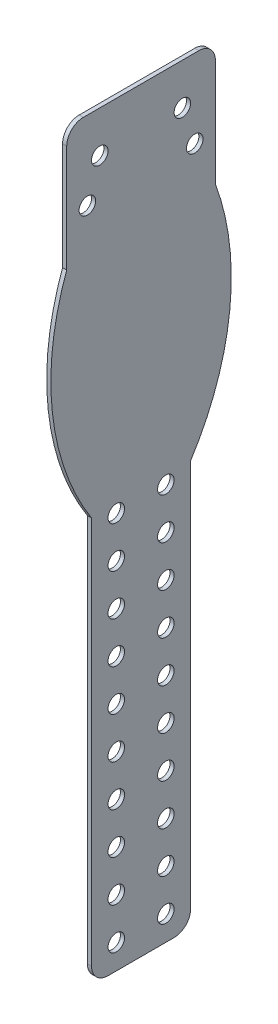
SolidWorks part; units mm, degrees
material "PVC 0.007 Plasticized"
ref_plane "Front Plane" through (0, 0, 0) normal (0, 0, 1) x (1, 0, 0)
ref_plane "Top Plane" through (0, 0, 0) normal (0, 1, 0) x (1, 0, 0)
ref_plane "Right Plane" through (0, 0, 0) normal (1, 0, 0) x (0, 0, -1)
sketch "Sketch1" plane through (0, 0, 0) normal (1, 0, 0) x (0, 0, -1)
  line L0 (12, -183) -> (12, -85)
  line L1 (-18, 0) -> (18, 0)
  line L2 (-18, 0) -> (-18, -183) construction
  line L3 (-18, -183) -> (18, -183) construction
  line L4 (18, 0) -> (18, -183) construction
  line L5 (-18, 0) -> (18, -183) construction
  line L6 (-18, -183) -> (18, 0) construction
  line L7 (-12, -183) -> (-12, -85)
  line L8 (12, -85) -> (-12, -85) construction
  line L9 (18, -30) -> (-18, -30) construction
  line L10 (18, 0) -> (18, -30)
  line L11 (-18, 0) -> (-18, -30)
  line L12 (-21.8408, -51.4826) -> (21.8408, -51.4826) construction
  line L13 (12, -183) -> (-12, -183)
  arc A0 (18, -30) -> (12, -85) centre (-40.1592, -51.4826) cw
  arc A1 (-18, -30) -> (-12, -85) centre (40.1592, -51.4826) ccw
  point P4 (0, -91.5)
  point P5 (0, 0)
  point P10 (0, -85)
  dimension "D6" = 62
  dimension "D7" = 62
  dimension "D1" = 30
  dimension "D2" = 36
  dimension "D3" = 24
  dimension "D4" = 183
  dimension "D5" = 55
  dimension "D8" = 43.6815
extrude "Boss-Extrude1" add sketch "Sketch1" along normal blind 1 contours L1 L10 A0 L0 L13 L7 A1 L11
hole_wizard "Ø4.0 (4) Diameter Hole3" positions "Sketch6" profile "Sketch7" hole size "Ø4.0" standard "ISO" end condition through all
sketch "Sketch6" plane through (0, 0, 0) normal (-1, 0, 0) x (0, 0, 1)
  point P0 (10, -10)
  point P3 (-10, -10)
sketch "Sketch7" plane through (0, -10, 10) normal (0, 1, 0) x (0, 0, 1)
  line L0 (0, 0) -> (0, 1)
  line L1 (0, 1) -> (2, 1)
  line L2 (2, 1) -> (2, 0)
  line L5 (2, 0) -> (0, 0)
  line L11 (0, -6.35) -> (0, 107.95) construction
  dimension "Thru Hole Dia." = 4
  dimension "Thru Hole Depth" = 1
hole_wizard "Ø4.0 (4) Diameter Hole2" positions "Sketch8" profile "Sketch9" hole size "Ø4.0" standard "ISO" end condition through all
sketch "Sketch8" plane through (0, 0, 0) normal (-1, 0, 0) x (0, 0, 1)
  point P4 (-13, -19)
  point P7 (13, -19)
sketch "Sketch9" plane through (0, -19, -13) normal (0, 1, 0) x (0, 0, 1)
  line L0 (0, 0) -> (0, 1)
  line L1 (0, 1) -> (2, 1)
  line L2 (2, 1) -> (2, 0)
  line L5 (2, 0) -> (0, 0)
  line L11 (0, -6.35) -> (0, 107.95) construction
  dimension "Thru Hole Dia." = 4
  dimension "Thru Hole Depth" = 1
hole_wizard "Ø4.0 (4) Diameter Hole1" positions "Sketch12" profile "Sketch11" hole size "Ø4.0" standard "ISO" end condition through all
sketch "Sketch12" plane through (1, 0, 0) normal (1, 0, 0) x (0, 0, -1)
  line L1 (12, -183) -> (-12, -183) construction
  point P0 (-6, -177)
  point P2 (6, -177)
  dimension "D1" = 12
  dimension "D2" = 6
  dimension "D3" = 6
sketch "Sketch11" plane through (1, -177, 6) normal (0, 1, 0) x (0, 0, -1)
  line L0 (0, 0) -> (0, 1)
  line L1 (0, 1) -> (2, 1)
  line L2 (2, 1) -> (2, 0)
  line L5 (2, 0) -> (0, 0)
  line L11 (0, -6.35) -> (0, 107.95) construction
  dimension "Thru Hole Dia." = 4
  dimension "Thru Hole Depth" = 1
pattern_linear "LPattern1" count 10 spacing 10 along (0, 1, 0) of "Ø4.0 (4) Diameter Hole1"
fillet "Fillet1" radius 4 4 edges at (0.5, -183, -12) (0.5, -183, 12) (0.5, 0, 18) (0.5, 0, -18)
